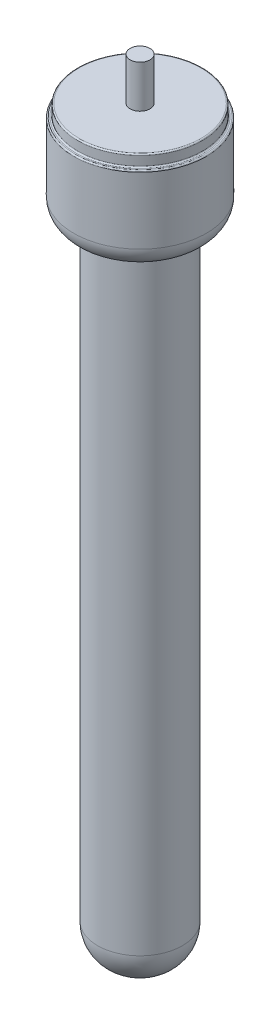
SolidWorks part; units mm, degrees
ref_plane "Front Plane" through (0, 0, 0) normal (0, 0, 1) x (1, 0, 0)
ref_plane "Top Plane" through (0, 0, 0) normal (0, 1, 0) x (1, 0, 0)
ref_plane "Right Plane" through (0, 0, 0) normal (1, 0, 0) x (0, 0, -1)
sketch "Sketch1" plane through (0, 0, 0) normal (0, 1, 0) x (1, 0, 0)
  circle A0 centre (0, 0) radius 12.5
  dimension "D1" = 25
extrude "Boss-Extrude1" add sketch "Sketch1" along normal blind 148.5
sketch "Sketch2" plane through (0, 0, 0) normal (0, -1, 0) x (1, 0, 0)
  circle A0 centre (0, 0) radius 8
  dimension "D1" = 16
extrude "Cut-Extrude1" cut sketch "Sketch2" against normal blind 121.5 flip side to cut
sketch "Sketch3" plane through (0, 148.5, 0) normal (0, 1, 0) x (1, 0, 0)
  circle A0 centre (0, 0) radius 1.875
  dimension "D1" = 3.75
extrude "Cut-Extrude2" cut sketch "Sketch3" against normal blind 8 flip side to cut
fillet "Fillet1" radius 4 1 edges at (0, 121.5, -12.5)
fillet "Fillet2" radius 7 1 edges at (0, 0, -8)
sketch "Sketch6" plane through (0, 140.5, 0) normal (0, 1, 0) x (1, 0, 0)
  circle A0 centre (0, 0) radius 11.75
  dimension "D1" = 23.5
extrude "Cut-Extrude3" cut sketch "Sketch6" against normal blind 2.2 flip side to cut
fillet "Fillet3" radius 0.25 3 edges at (0, 140.5, 11.75) (0, 138.3, 11.75) (0, 138.3, 12.5)
